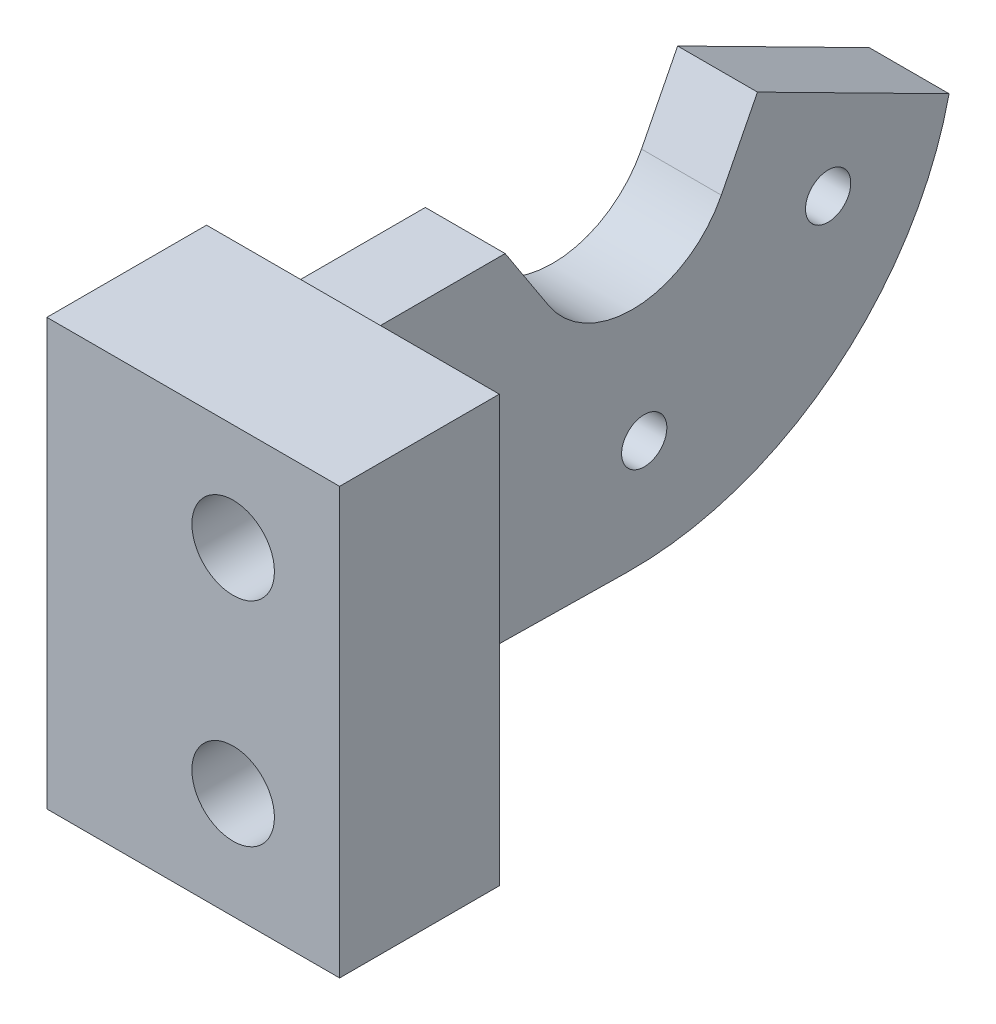
SolidWorks part; units mm, degrees
ref_plane "Front Plane" through (0, 0, 0) normal (0, 0, 1) x (1, 0, 0)
ref_plane "Top Plane" through (0, 0, 0) normal (0, 1, 0) x (1, 0, 0)
ref_plane "Right Plane" through (0, 0, 0) normal (1, 0, 0) x (0, 0, -1)
sketch "Sketch1" plane through (0, 0, 0) normal (0, 0, 1) x (1, 0, 0)
  line L1 (0, 0) -> (8, 0)
  line L2 (0, 0) -> (0, 16)
  line L3 (0, 16) -> (8, 16)
  line L4 (8, 0) -> (8, 16)
  circle A0 centre (4, 12) radius 1.55
  circle A1 centre (4, 4) radius 1.55
  point P10 (4, 0)
  dimension "D1" = 3.1
  dimension "D5" = 4
  dimension "D2" = 8
  dimension "D3" = 8
  dimension "D4" = 4
extrude "Boss-Extrude1" add sketch "Sketch1" along normal blind 6
sketch "Sketch2" plane through (0, 0, 0) normal (0, 0, -1) x (-1, 0, 0)
  line L1 (-0.7668, 12) -> (-2.3834, 14.8)
  line L2 (-2.3834, 14.8) -> (-5.6166, 14.8)
  line L3 (-5.6166, 14.8) -> (-7.2332, 12)
  line L4 (-7.2332, 12) -> (-5.6166, 9.2)
  line L5 (-5.6166, 9.2) -> (-2.3834, 9.2)
  line L6 (-2.3834, 9.2) -> (-0.7668, 12)
  line L7 (-0.7668, 4) -> (-2.3834, 6.8)
  line L8 (-2.3834, 6.8) -> (-5.6166, 6.8)
  line L9 (-5.6166, 6.8) -> (-7.2332, 4)
  line L10 (-7.2332, 4) -> (-5.6166, 1.2)
  line L11 (-5.6166, 1.2) -> (-2.3834, 1.2)
  line L12 (-2.3834, 1.2) -> (-0.7668, 4)
  circle A0 centre (-4, 12) radius 2.8 construction
  circle A1 centre (-4, 4) radius 2.8 construction
  dimension "D1" = 5.6
extrude "Cut-Extrude1" cut sketch "Sketch2" against normal blind 2.5
sketch "Sketch3" plane through (0, 0, 0) normal (-1, 0, 0) x (0, 0, 1)
  line L0 (6, 16) -> (6, 0) construction
  line L5 (-13, 12) -> (-20.3572, 8.2672) construction
  line L6 (-13, 12) -> (-13.4459, 3.7621) construction
  line L7 (-17.7016, 12.9786) -> (-24.9031, 9.3249)
  line L9 (-6.0887, 7.4948) -> (-13, 12) construction
  line L10 (-16.3442, 10.3033) -> (-17.7016, 12.9786)
  line L11 (-9.8585, 9.9522) -> (-8.2203, 12.4654)
  line L12 (0, 16) -> (0, 0) construction
  line L13 (-17.7016, 12.9786) -> (-17.0074, 15.1085) construction
  line L14 (-8.2203, 12.4654) -> (-8.6804, 14.6577) construction
  line L15 (-12.811, -0.1985) -> (0, 0)
  line L16 (0, 0) -> (6, 0)
  line L17 (6, 0) -> (6, 16)
  line L18 (6, 16) -> (0, 16) construction
  line L21 (-8.2203, 12.4654) -> (0, 12.4654)
  line L22 (0, 12.4654) -> (0, 16)
  arc A1 (-24.9031, 9.3249) -> (-12.811, -0.1985) centre (-13, 12) ccw
  circle A3 centre (-20.3572, 8.2672) radius 0.85
  circle A4 centre (-13.4459, 3.7621) radius 0.85
  circle A5 centre (-6.0887, 7.4948) radius 0.85
  arc A7 (-16.3442, 10.3033) -> (-9.8585, 9.9522) centre (-13, 12) ccw
  circle A8 centre (-13, 12) radius 2.9017 construction
  circle A9 centre (-12, 30.473) radius 16.1599 construction
  circle A10 centre (-13, 12) radius 12.2 construction
  circle A11 centre (-14, 51.3775) radius 16.1599 construction
  circle A12 centre (-12, 30.473) radius 5.5533 construction
  line M17 (0, 16) -> (0, 0)
  line M18 (0, 0) -> (6, 0)
  line M19 (6, 0) -> (6, 16)
  line M20 (6, 16) -> (0, 16)
  dimension "D1" = 1.7
  dimension "D2" = 8.25
  dimension "D5" = 3.75
  dimension "D8" = 12.2
  dimension "D9" = 5.8033
  dimension "D10" = 32.3198
  dimension "D14" = 32.3198
  dimension "D15" = 11.1066
  dimension "D4" = 60
  dimension "D6" = 3
  dimension "D7" = 3
  dimension "D11" = 18.5
  dimension "D12" = 13
  dimension "D13" = 12
  dimension "D16" = 21
  dimension "D17" = 20
  dimension "D18" = 18
  dimension "D3" = 3
extrude "Boss-Extrude2" add sketch "Sketch3" along normal blind 3 contours M20 M17 M18 M19 | A7 L10 L7 A1 L15 L21 L11 A5 A4 A3 M17
